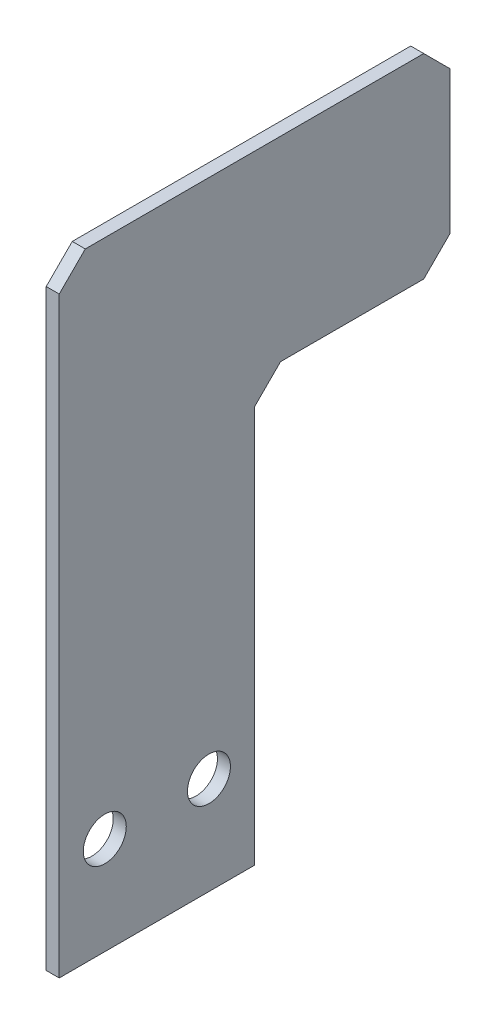
SolidWorks part; units mm, degrees
ref_plane "Front Plane" through (0, 0, 0) normal (0, 0, 1) x (1, 0, 0)
ref_plane "Top Plane" through (0, 0, 0) normal (0, 1, 0) x (1, 0, 0)
ref_plane "Right Plane" through (0, 0, 0) normal (1, 0, 0) x (0, 0, -1)
sketch "Sketch1" plane through (0, 0, 0) normal (1, 0, 0) x (0, 0, -1)
  line L0 (21.0306, 39.3851) -> (48.9706, 39.3851)
  line L1 (-17.0694, 77.4851) -> (48.9706, 77.4851)
  line L2 (-22.1494, 72.4051) -> (-22.1494, -43.1649)
  line L3 (-22.1494, -43.1649) -> (15.9506, -43.1649)
  line L4 (15.9506, 34.3051) -> (15.9506, -43.1649)
  line L5 (54.0506, 72.4051) -> (54.0506, 44.4651)
  line L6 (15.9506, 34.3051) -> (21.0306, 39.3851)
  line L7 (48.9706, 39.3851) -> (54.0506, 44.4651)
  line L8 (48.9706, 77.4851) -> (54.0506, 72.4051)
  line L9 (-22.1494, 72.4051) -> (-17.0694, 77.4851)
  point P0 (-22.1494, 77.4851)
  point P4 (54.0506, 77.4851)
  point P5 (54.0506, 39.3851)
  point P6 (15.9506, 39.3851)
  dimension "D1" = 38.1
  dimension "D2" = 120.65
  dimension "D3" = 82.55
extrude "Boss-Extrude1" add sketch "Sketch1" along normal blind 2.54
sketch "Sketch2" plane through (2.54, 0, 0) normal (1, 0, 0) x (0, 0, -1)
  line L0 (-22.1494, -43.1649) -> (15.9506, -43.1649) construction
  circle A0 centre (-13.2594, -24.1149) radius 4.191
  circle A1 centre (7.0606, -24.1149) radius 4.191
  point P6 (-3.0994, -43.1649)
  dimension "D1" = 20.32
  dimension "D2" = 10.16
  dimension "D3" = 19.05
  dimension "D4" = 19.05
extrude "Cut-Extrude1" cut sketch "Sketch2" against normal through all
